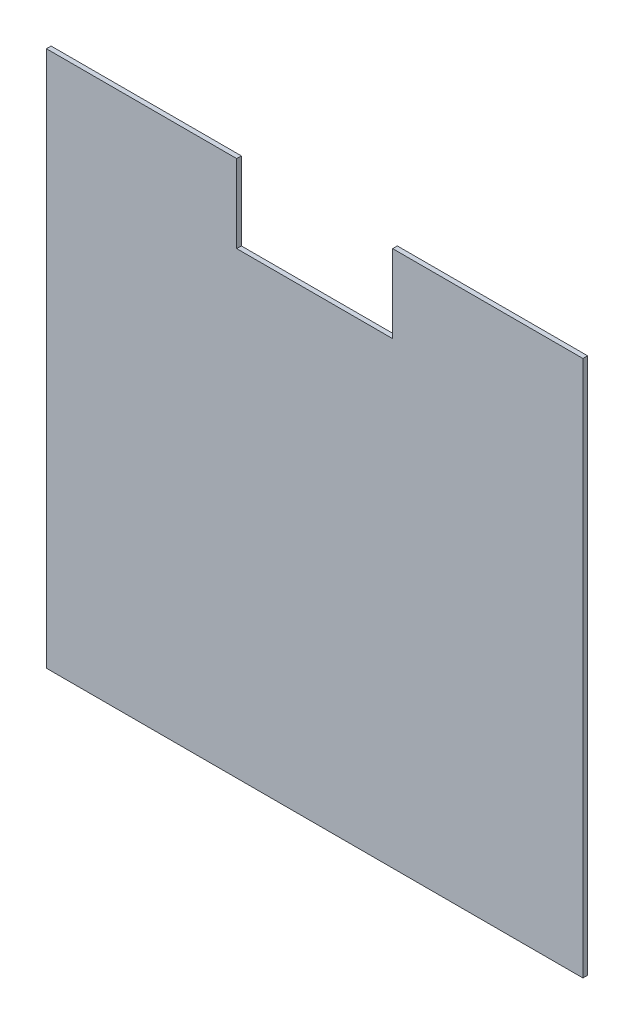
SolidWorks part; units mm, degrees
ref_plane "Piano frontale" through (0, 0, 0) normal (0, 0, 1) x (1, 0, 0)
ref_plane "Piano superiore" through (0, 0, 0) normal (0, 1, 0) x (1, 0, 0)
ref_plane "Piano destro" through (0, 0, 0) normal (1, 0, 0) x (0, 0, -1)
sketch "Schizzo1" plane through (0, 0, 0) normal (0, 0, 1) x (1, 0, 0)
  line L0 (0, 0) -> (0, 344)
  line L1 (0, 344) -> (122, 344)
  line L2 (344, 344) -> (344, 0)
  line L3 (344, 0) -> (0, 0)
  line L4 (122, 344) -> (122, 294)
  line L5 (122, 294) -> (222, 294)
  line L6 (222, 294) -> (222, 344)
  line L7 (222, 344) -> (344, 344)
  dimension "D1" = 344
  dimension "D2" = 344
  dimension "D3" = 100
  dimension "D4" = 50
extrude "Estrusione-Estrusione1" add sketch "Schizzo1" along normal blind 3
